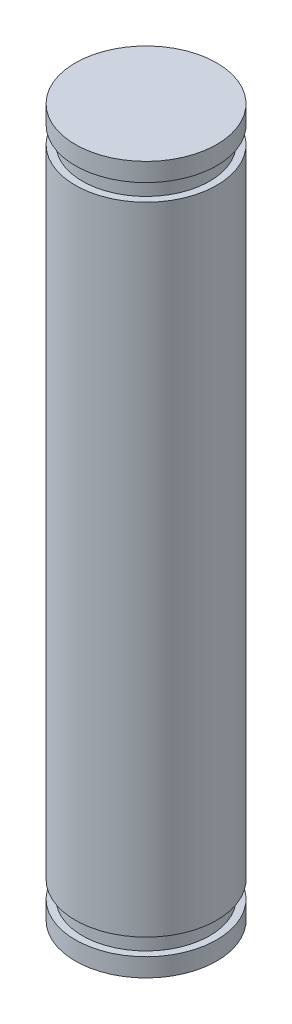
SolidWorks part; units mm, degrees
ref_plane "前视基准面" through (0, 0, 0) normal (0, 0, 1) x (1, 0, 0)
ref_plane "上视基准面" through (0, 0, 0) normal (0, 1, 0) x (1, 0, 0)
ref_plane "右视基准面" through (0, 0, 0) normal (1, 0, 0) x (0, 0, -1)
sketch "草图1" plane through (0, 0, 0) normal (0, 0, 1) x (1, 0, 0)
  line L0 (0, 0) -> (0, 50) construction
  line L1 (0, 0) -> (5, 0)
  line L2 (5, 0) -> (5, 1.3)
  line L3 (5, 1.3) -> (4.5, 1.3)
  line L4 (4.5, 1.3) -> (4.5, 2.5)
  line L5 (4.5, 2.5) -> (5, 2.5)
  line L6 (5, 2.5) -> (5, 47.5)
  line L7 (5, 47.5) -> (4.5, 47.5)
  line L8 (4.5, 47.5) -> (4.5, 48.7)
  line L9 (4.5, 48.7) -> (5, 48.7)
  line L10 (5, 48.7) -> (5, 50)
  line L11 (5, 50) -> (0, 50)
  line L12 (0, 0) -> (0, 50)
revolve "旋转1" add sketch "草图1" angle 360 about L0
